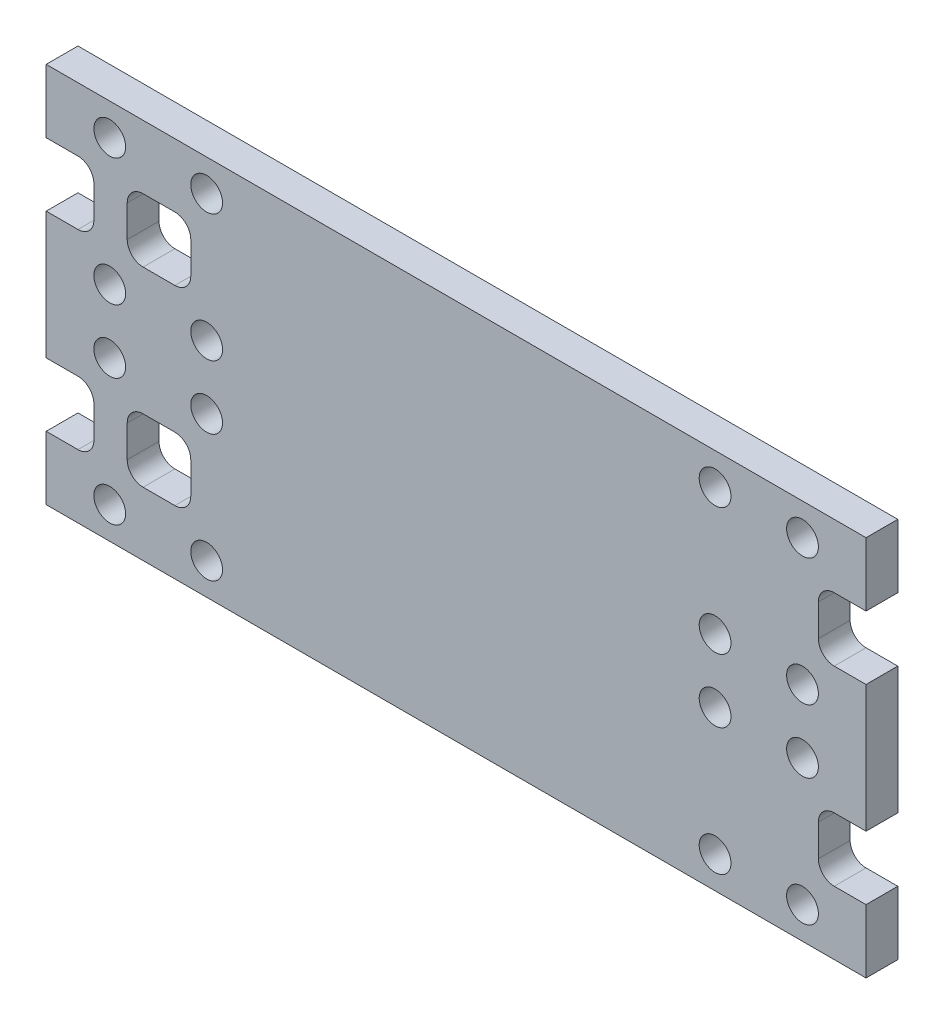
SolidWorks part; units mm, degrees
material "自訂玻璃纖維"
ref_plane "前基準面" through (0, 0, 0) normal (0, 0, 1) x (1, 0, 0)
ref_plane "上基準面" through (0, 0, 0) normal (0, 1, 0) x (1, 0, 0)
ref_plane "右基準面" through (0, 0, 0) normal (1, 0, 0) x (0, 0, -1)
sketch "草圖14" plane through (0, 0, 0) normal (0, 0, 1) x (1, 0, 0)
  line L0 (-33.7214, -5) -> (-33.7214, -7)
  line L1 (-36.7214, 0) -> (14.8786, 0)
  line L2 (-36.7214, 0) -> (-36.7214, -4)
  line L3 (-36.7214, -24) -> (14.8786, -24)
  line L4 (14.8786, 0) -> (14.8786, -4)
  line L5 (-36.7214, -4) -> (-34.7214, -4)
  line L6 (-36.7214, -16) -> (-34.7214, -16)
  line L7 (-36.7214, -8) -> (-34.7214, -8)
  line L8 (-36.7214, -8) -> (-36.7214, -16)
  line L9 (-33.7214, -17) -> (-33.7214, -19)
  line L10 (-36.7214, -20) -> (-34.7214, -20)
  line L11 (-36.7214, -20) -> (-36.7214, -24)
  line L12 (14.8786, -8) -> (14.8786, -16)
  line L13 (14.8786, -20) -> (12.8786, -20)
  line L14 (11.8786, -17) -> (11.8786, -19)
  line L15 (-30.6219, -4) -> (-28.6219, -4)
  line L16 (14.8786, -8) -> (12.8786, -8)
  line L17 (14.8786, -16) -> (12.8786, -16)
  line L18 (14.8786, -4) -> (12.8786, -4)
  line L19 (11.8786, -5) -> (11.8786, -7)
  line L20 (14.8786, -20) -> (14.8786, -24)
  line L21 (-30.6219, -8) -> (-28.6219, -8)
  line L22 (-27.6219, -5) -> (-27.6219, -7)
  line L23 (-31.6219, -5) -> (-31.6219, -7)
  line L24 (-27.6219, -17) -> (-27.6219, -19)
  line L25 (-31.6219, -17) -> (-31.6219, -19)
  line L26 (-30.6219, -16) -> (-28.6219, -16)
  line L27 (-30.6219, -20) -> (-28.6219, -20)
  circle A0 centre (10.8786, -14) radius 1
  circle A1 centre (5.3781, -14) radius 1
  circle A2 centre (5.3781, -22) radius 1
  circle A3 centre (10.8786, -22) radius 1
  circle A4 centre (-26.6219, -14) radius 1
  circle A5 centre (-32.7219, -14) radius 1
  circle A6 centre (-32.7219, -22) radius 1
  circle A7 centre (-26.6219, -22) radius 1
  circle A8 centre (5.3781, -2) radius 1
  circle A9 centre (5.3781, -10) radius 1
  circle A10 centre (10.8786, -10) radius 1
  circle A11 centre (-32.7214, -2) radius 1
  circle A12 centre (-26.6219, -2) radius 1
  circle A13 centre (-32.7214, -10) radius 1
  circle A14 centre (-26.6219, -10) radius 1
  circle A15 centre (10.8786, -2) radius 1
  arc A16 (-34.7214, -4) -> (-33.7214, -5) centre (-34.7214, -5) cw
  arc A17 (-33.7214, -7) -> (-34.7214, -8) centre (-34.7214, -7) cw
  arc A18 (-34.7214, -16) -> (-33.7214, -17) centre (-34.7214, -17) cw
  arc A19 (-33.7214, -19) -> (-34.7214, -20) centre (-34.7214, -19) cw
  arc A20 (11.8786, -19) -> (12.8786, -20) centre (12.8786, -19) ccw
  arc A21 (12.8786, -16) -> (11.8786, -17) centre (12.8786, -17) ccw
  arc A22 (11.8786, -7) -> (12.8786, -8) centre (12.8786, -7) ccw
  arc A23 (12.8786, -4) -> (11.8786, -5) centre (12.8786, -5) ccw
  arc A24 (-27.6219, -7) -> (-28.6219, -8) centre (-28.6219, -7) cw
  arc A25 (-28.6219, -4) -> (-27.6219, -5) centre (-28.6219, -5) cw
  arc A26 (-30.6219, -4) -> (-31.6219, -5) centre (-30.6219, -5) ccw
  arc A27 (-31.6219, -7) -> (-30.6219, -8) centre (-30.6219, -7) ccw
  arc A28 (-28.6219, -16) -> (-27.6219, -17) centre (-28.6219, -17) cw
  arc A29 (-27.6219, -19) -> (-28.6219, -20) centre (-28.6219, -19) cw
  arc A30 (-30.6219, -16) -> (-31.6219, -17) centre (-30.6219, -17) ccw
  arc A31 (-31.6219, -19) -> (-30.6219, -20) centre (-30.6219, -19) ccw
  point P26 (-36.7214, 0)
  point P29 (14.8786, -24)
  point P32 (14.8786, 0)
  point P33 (-36.7214, 0)
  point P34 (14.8786, -24)
  dimension "D3" = 2
  dimension "D5" = 32
  dimension "D6" = 6.1
  dimension "D8" = 32
  dimension "D9" = 6.1
  dimension "D10" = 32
  dimension "D11" = 32
  dimension "D12" = 14
  dimension "D13" = 1
  dimension "D14" = 4
  dimension "D15" = 8
  dimension "D16" = 8
  dimension "D17" = 2
  dimension "D18" = 4
  dimension "D19" = 8
  dimension "D1" = 51.6
  dimension "D2" = 24
  dimension "D4" = 8
  dimension "D7" = 8
  dimension "D20" = 2
  dimension "D21" = 4
  dimension "D22" = 2
extrude "填料-伸長1" add sketch "草圖14" along normal blind 2
